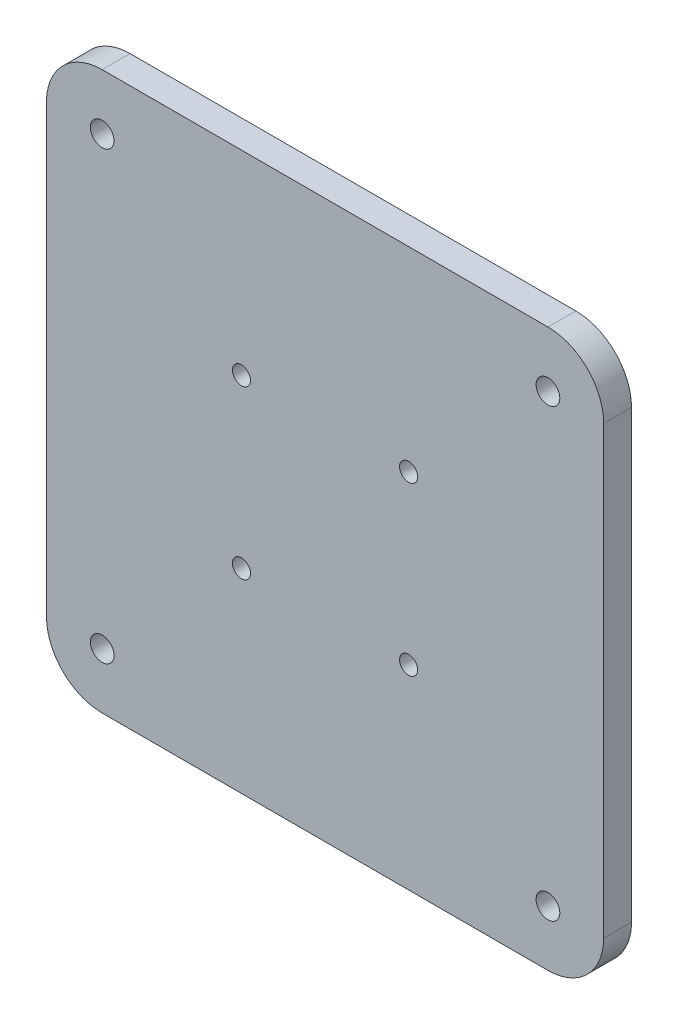
SolidWorks part; units mm, degrees
ref_plane "前视基准面" through (0, 0, 0) normal (0, 0, 1) x (1, 0, 0)
ref_plane "上视基准面" through (0, 0, 0) normal (0, 1, 0) x (1, 0, 0)
ref_plane "右视基准面" through (0, 0, 0) normal (1, 0, 0) x (0, 0, -1)
other "Configuration Table"
sketch "草图1" plane through (0, 0, 0) normal (0, 0, 1) x (1, 0, 0)
  line L0 (0, 0) -> (284.1069, 0) construction
  line L1 (-100, 100) -> (100, 100)
  line L2 (-100, 100) -> (-100, -100)
  line L3 (-100, -100) -> (100, -100)
  line L4 (100, 100) -> (100, -100)
  line L5 (0, 0) -> (0, 194.938) construction
  circle A0 centre (30, 30) radius 3.25
  circle A1 centre (30, -30) radius 3.25
  circle A2 centre (-30, 30) radius 3.25
  circle A3 centre (-30, -30) radius 3.25
  circle A4 centre (80, 80) radius 4.25
  circle A6 centre (80, -80) radius 4.25
  circle A7 centre (-80, -80) radius 4.25
  circle A8 centre (-80, 80) radius 4.25
  dimension "D3" = 6.5
  dimension "D6" = 8.5
  dimension "D1" = 200
  dimension "D2" = 200
  dimension "D4" = 30
  dimension "D5" = 30
  dimension "D7" = 80
  dimension "D8" = 80
extrude "凸台-拉伸1" add sketch "草图1" along normal blind 10 contours L4 L3 L2 L1 | A1 | A3 | A2 | A0 | A6 | A7 | A8 | A4
fillet "圆角1" radius 20 4 edges at (-100, 100, 5) (-100, -100, 5) (100, -100, 5) (100, 100, 5)
